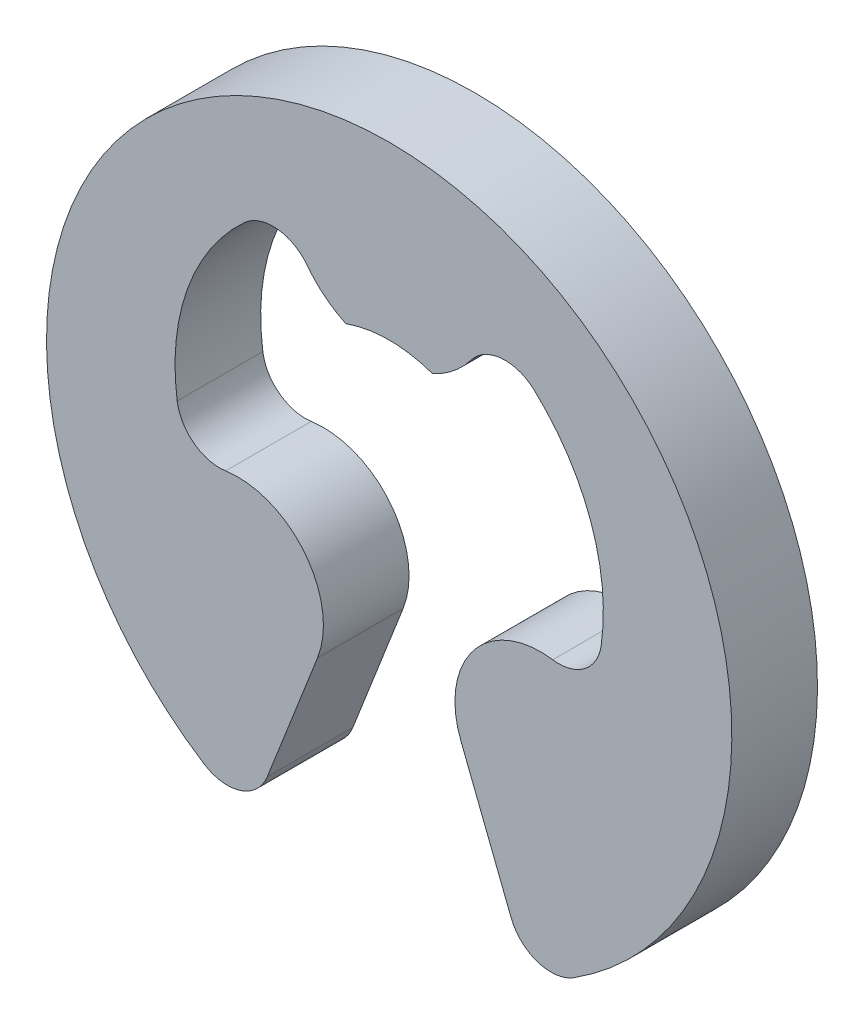
SolidWorks part; units mm, degrees
ref_plane "Plan de face" through (0, 0, 0) normal (0, 0, 1) x (1, 0, 0)
ref_plane "Plan de dessus" through (0, 0, 0) normal (0, 1, 0) x (1, 0, 0)
ref_plane "Plan de droite" through (0, 0, 0) normal (1, 0, 0) x (0, 0, -1)
sketch "Esquisse1" plane through (0, 0, 0) normal (0, 0, 1) x (1, 0, 0)
  line L0 (0, -16.3763) -> (0, 18.0474) construction
  line L1 (0, 0) -> (-2.1244, -2.1244) construction
  line L2 (-0.4184, -1.0665) -> (-0.7119, -1.8145)
  line L3 (0.4184, -1.0665) -> (0.7119, -1.8145)
  arc A0 (1.0796, -1.9336) -> (-1.0796, -1.9336) centre (0, -0.25) ccw
  arc A1 (0.2531, 0.706) -> (-0.2531, 0.706) centre (0, 0) ccw
  circle A2 centre (0, 0) radius 1.25 construction
  arc A3 (-1.0796, -1.9336) -> (-0.7119, -1.8145) centre (-0.9446, -1.7232) ccw
  arc A4 (-0.4779, 0.8872) -> (-0.2531, 0.706) centre (0, 1.25) ccw
  arc A5 (-0.4184, -1.0665) -> (-0.9546, -0.3889) centre (-0.8839, -0.8839) ccw
  circle A6 centre (0, 0) radius 0.75 construction
  arc A7 (-0.8462, 0.92) -> (-1.2374, -0.1768) centre (0, 0) ccw
  arc A8 (-0.4779, 0.8872) -> (-0.8462, 0.92) centre (-0.677, 0.736) ccw
  arc A9 (-1.2374, -0.1768) -> (-0.9546, -0.3889) centre (-0.9899, -0.1414) ccw
  arc A10 (0.4779, 0.8872) -> (0.2531, 0.706) centre (0, 1.25) cw
  arc A11 (0.4779, 0.8872) -> (0.8462, 0.92) centre (0.677, 0.736) cw
  arc A12 (0.8462, 0.92) -> (1.2374, -0.1768) centre (0, 0) cw
  arc A13 (1.2374, -0.1768) -> (0.9546, -0.3889) centre (0.9899, -0.1414) cw
  arc A14 (0.4184, -1.0665) -> (0.9546, -0.3889) centre (0.8839, -0.8839) cw
  arc A15 (1.0796, -1.9336) -> (0.7119, -1.8145) centre (0.9446, -1.7232) cw
  point P22 (-0.5825, 1.106)
  point P25 (-1.1596, -0.4668)
  dimension "D1" = 4
  dimension "D2" = 1.5
  dimension "D6" = 0.6
  dimension "D7" = 0.25
  dimension "D8" = 0.25
  dimension "D3" = 0.25
  dimension "D5" = 45
  dimension "D4" = 0.5
extrude "Boss.-Extru.1" add sketch "Esquisse1" along normal blind 0.5
